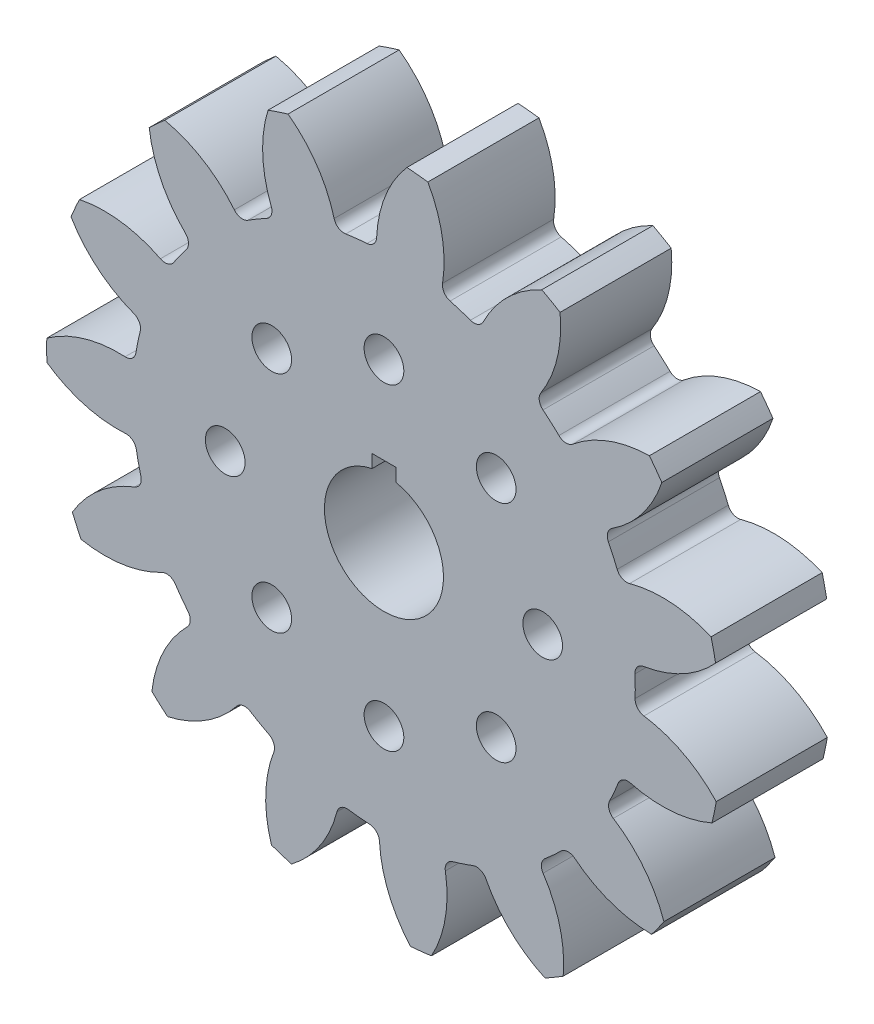
SolidWorks part; units mm, degrees
material "AISI 304"
ref_plane "Alzado" through (0, 0, 0) normal (0, 0, 1) x (1, 0, 0)
ref_plane "Planta" through (0, 0, 0) normal (0, 1, 0) x (1, 0, 0)
ref_plane "Vista lateral" through (0, 0, 0) normal (1, 0, 0) x (0, 0, -1)
sketch "Sketch1" plane through (0, 0, 0) normal (0, 0, 1) x (1, 0, 0)
  circle A0 centre (0, 0) radius 42.5
  dimension "D1" = 85
extrude "Boss-Extrude1" add sketch "Sketch1" along normal blind 14
sketch "Sketch2" plane through (0, 0, 14) normal (0, 0, 1) x (1, 0, 0)
  arc A0 (-2.144, 31.594) -> (-4.8133, 31.2987) centre (0, 0) ccw
  arc A2 (2.89, 42.4016) -> (-12.0879, 40.7447) centre (0, 0) ccw
  arc A3 (2.89, 42.4016) -> (-0.9249, 32.8435) centre (14.6377, 32.1723) ccw
  arc A4 (-12.0879, 40.7447) -> (-6.276, 32.2515) centre (-21.3157, 28.1951) cw
  arc A5 (-2.144, 31.594) -> (-0.9249, 32.8435) centre (-2.2326, 32.8999) ccw
  arc A6 (-4.8133, 31.2987) -> (-6.276, 32.2515) centre (-5.0123, 32.5924) cw
  dimension "D1" = 85
  dimension "D3" = 63.3333
  dimension "D4" = 1.3089
extrude "Cut-Extrude2" cut sketch "Sketch2" against normal blind 14
pattern_circular "CirPattern1" count 15 over 360 about axis through (0, 0, 0) along (0, 0, 1) of "Cut-Extrude2"
sketch "Sketch3" plane through (0, 0, 0) normal (0, 0, -1) x (-1, 0, 0)
  circle A0 centre (0, 0) radius 25
  dimension "D1" = 50
extrude "Cut-Extrude3" cut sketch "Sketch3" against normal blind 3
sketch "Sketch4" plane through (0, 0, 3) normal (0, 0, -1) x (-1, 0, 0)
  circle A0 centre (0, 0) radius 7.5
  dimension "D1" = 15
extrude "Cut-Extrude4" cut sketch "Sketch4" against normal blind 12
sketch "Sketch5" plane through (0, 0, 3) normal (0, 0, -1) x (-1, 0, 0)
  circle A0 centre (0, 0) radius 7.5
  circle A2 centre (0, 0) radius 15
  dimension "D1" = 15
  dimension "D2" = 30
extrude "Boss-Extrude2" add sketch "Sketch5" along normal blind 3
sketch "Sketch6" plane through (0, 0, 3) normal (0, 0, -1) x (-1, 0, 0)
  circle A0 centre (0, 20) radius 2.5
  circle A1 centre (14.1421, 14.1421) radius 2.5
  circle A2 centre (20, 0) radius 2.5
  circle A3 centre (14.1421, -14.1421) radius 2.5
  circle A4 centre (0, -20) radius 2.5
  circle A5 centre (-14.1421, -14.1421) radius 2.5
  circle A6 centre (-20, 0) radius 2.5
  circle A7 centre (-14.1421, 14.1421) radius 2.5
  point P20 (0, 0)
  dimension "D1" = 5
  dimension "D2" = 20
  dimension "D3" = 8
extrude "Cut-Extrude7" cut sketch "Sketch6" against normal through all
sketch "Sketch7" plane through (0, 0, 0) normal (0, 0, -1) x (-1, 0, 0)
  line L1 (-1.5, 6) -> (1.5, 6)
  line L2 (-1.5, 6) -> (-1.5, 9)
  line L3 (-1.5, 9) -> (1.5, 9)
  line L4 (1.5, 6) -> (1.5, 9)
  line L5 (-1.5, 6) -> (1.5, 9) construction
  line L6 (-1.5, 9) -> (1.5, 6) construction
  circle A0 centre (0, 0) radius 7.5 construction
  point P0 (0, 7.5)
  dimension "D1" = 3
  dimension "D2" = 3
extrude "Cut-Extrude8" cut sketch "Sketch7" against normal through all
